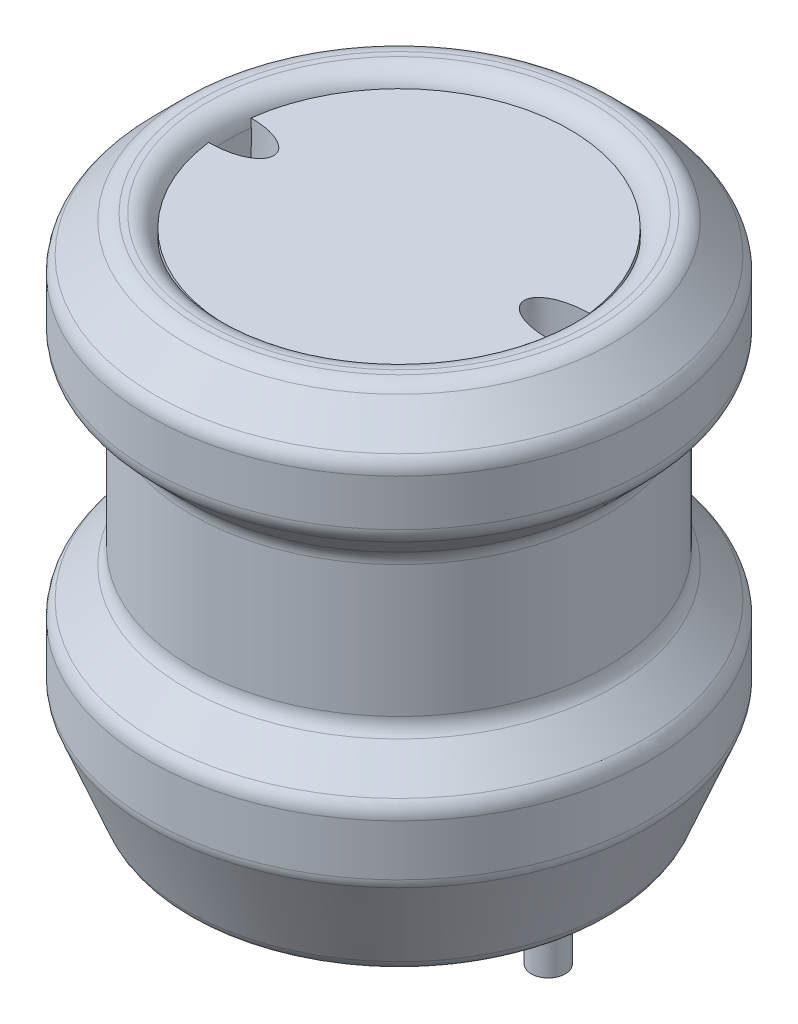
SolidWorks part; units mm, degrees
ref_plane "Спереди" through (0, 0, 0) normal (0, 0, 1) x (1, 0, 0)
ref_plane "Сверху" through (0, 0, 0) normal (0, 1, 0) x (1, 0, 0)
ref_plane "Справа" through (0, 0, 0) normal (1, 0, 0) x (0, 0, -1)
sketch "Эскиз1" plane through (0, 0, 0) normal (0, 1, 0) x (1, 0, 0)
  circle A0 centre (-3.5, 0) radius 0.4
  circle A1 centre (3.5, 0) radius 0.4
extrude "Бобышка-Вытянуть1" add sketch "Эскиз1" along normal blind 1.5 from offset 0.5 offset against normal yes
sketch "Эскиз3" plane through (0, 0, 0) normal (0, 0, 1) x (1, 0, 0)
  line L0 (0, 3.5) -> (-5.85, 3.5) construction
  line L1 (0, 1) -> (-5.85, 1) construction
  line L2 (0, 1) -> (0, 13) construction
  line L3 (0, 13) -> (-5.85, 13) construction
  line L4 (-5.85, 1) -> (-5.85, 13) construction
  line L5 (-5.85, 5) -> (0, 5) construction
  line L6 (-5.85, 6) -> (0, 6) construction
  line L7 (-5.85, 12) -> (0, 12) construction
  line L8 (-5.85, 10.5) -> (0, 10.5) construction
  line L9 (-5.85, 9.5) -> (0, 9.5) construction
  line L10 (-4.85, 13) -> (-4.85, 1) construction
  line L11 (0, 13) -> (-4.85, 13)
  line L12 (-4.85, 13) -> (-5.85, 12)
  line L13 (-5.85, 12) -> (-5.85, 10.5)
  line L14 (-5.85, 10.5) -> (-4.85, 9.5)
  line L15 (-4.85, 9.5) -> (-4.85, 6)
  line L16 (-4.85, 6) -> (-5.85, 5)
  line L17 (-5.85, 5) -> (-5.85, 3.5)
  line L18 (-5.85, 3.5) -> (-4.85, 1)
  line L19 (-4.85, 1) -> (0, 1)
  line L20 (0, 1) -> (0, 13)
revolve "Повернуть1" add sketch "Эскиз3" angle 360 about L20
sketch "Эскиз5" plane through (0, 13, 0) normal (0, 1, 0) x (1, 0, 0)
  circle A0 centre (0, 0) radius 4
  point P3 (0, 0)
extrude "Бобышка-Вытянуть2" add sketch "Эскиз5" along normal blind 3 from offset 2 separate body offset against normal yes
combine bodies "Соединить1" operation type subtract main body 105 bodies to subtract 106
sketch "Эскиз6" plane through (0, 11, 0) normal (0, 1, 0) x (1, 0, 0)
  circle A0 centre (0, 0) radius 4
extrude "Бобышка-Вытянуть3" add sketch "Эскиз6" along normal blind 1.7 separate body
sketch "Эскиз7" plane through (0, 12.7, 0) normal (0, 1, 0) x (1, 0, 0)
  line L0 (-4, 0) -> (4, 0) construction
  line L1 (-4, 0.5) -> (-4, -0.5)
  line L2 (-4, -0.5) -> (-3, -0.5) construction
  line L3 (-4, 0.5) -> (-3, 0.5) construction
  line L4 (-4, 0) -> (-2.5, 0) construction
  line L5 (-4, 0.5) -> (-3, 0.5) construction
  line L6 (-3, 0.5) -> (-2.5, 0) construction
  line L7 (-2.5, 0) -> (-3, -0.5) construction
  line L8 (-3, -0.5) -> (-4, -0.5) construction
  line L9 (4, 0.5) -> (4, -0.5)
  line L10 (4, 0.5) -> (3, 0.5) construction
  line L11 (3, 0.5) -> (2.5, 0) construction
  line L12 (2.5, 0) -> (3, -0.5) construction
  line L13 (3, -0.5) -> (4, -0.5) construction
  line L14 (4, 0.5) -> (3, 0.5) construction
  line L15 (3, 0.5) -> (2.5, 0) construction
  line L16 (2.5, 0) -> (3, -0.5) construction
  line L17 (3, -0.5) -> (4, -0.5) construction
  circle A0 centre (0, 0) radius 4 construction
  spline S0 degree 4 poles (-4, 0.5) (-3, 0.5) (-2.5, 0) (-3, -0.5) (-4, -0.5) knots 0 0 0 0 0 1 1 1 1 1
  spline S1 degree 4 poles (4, 0.5) (3, 0.5) (2.5, 0) (3, -0.5) (4, -0.5) knots 0 0 0 0 0 1 1 1 1 1
extrude "Бобышка-Вытянуть4" add sketch "Эскиз7" along normal blind 1.7 from offset 1.5 separate body offset against normal yes
combine bodies "Соединить2" operation type subtract main body 108 bodies to subtract 110 109
fillet "Скругление1" radius 0.5 9 edges at (0, 3.5, -5.85) (0, 1, -4.85) (0, 9.5, -4.85) (0, 6, -4.85) (0, 13, -4.85) (0, 13, -4) (0, 12, -5.85) (0, 10.5, -5.85) (0, 5, -5.85)
